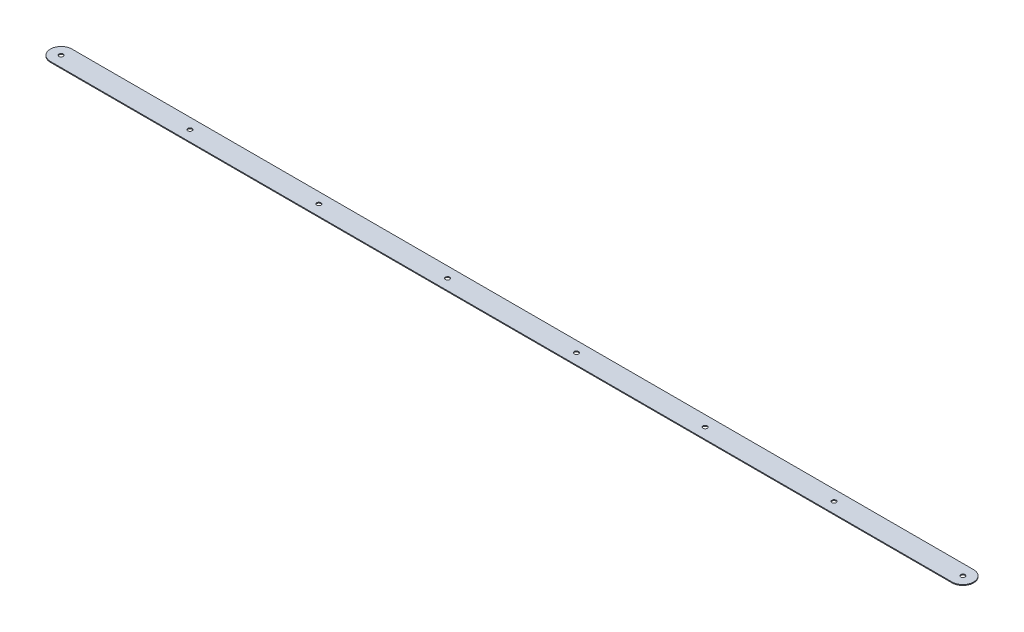
SolidWorks part; units mm, degrees
ref_plane "Front Plane" through (0, 0, 0) normal (0, 0, 1) x (1, 0, 0)
ref_plane "Top Plane" through (0, 0, 0) normal (0, 1, 0) x (1, 0, 0)
ref_plane "Right Plane" through (0, 0, 0) normal (1, 0, 0) x (0, 0, -1)
sketch "Sketch1" plane through (0, 0, 0) normal (0, 1, 0) x (1, 0, 0)
  line L0 (0, 0) -> (1050, 0) construction
  line L1 (0, 0) -> (1050, 0) construction
  line L2 (0, 12.5) -> (1050, 12.5)
  line L3 (0, -12.5) -> (1050, -12.5)
  circle A0 centre (0, 0) radius 2.5
  circle A1 centre (150, 0) radius 2.5
  circle A2 centre (300, 0) radius 2.5
  circle A3 centre (450, 0) radius 2.5
  circle A4 centre (600, 0) radius 2.5
  circle A5 centre (750, 0) radius 2.5
  circle A6 centre (900, 0) radius 2.5
  circle A7 centre (1050, 0) radius 2.5
  arc A8 (0, 12.5) -> (0, -12.5) centre (0, 0) ccw
  arc A9 (1050, -12.5) -> (1050, 12.5) centre (1050, 0) ccw
  point P19 (525, 0)
  dimension "D1" = 5
  dimension "D2" = 1050
  dimension "D4" = 25
  dimension "D3" = 8
extrude "Boss-Extrude1" add sketch "Sketch1" along normal blind 1
